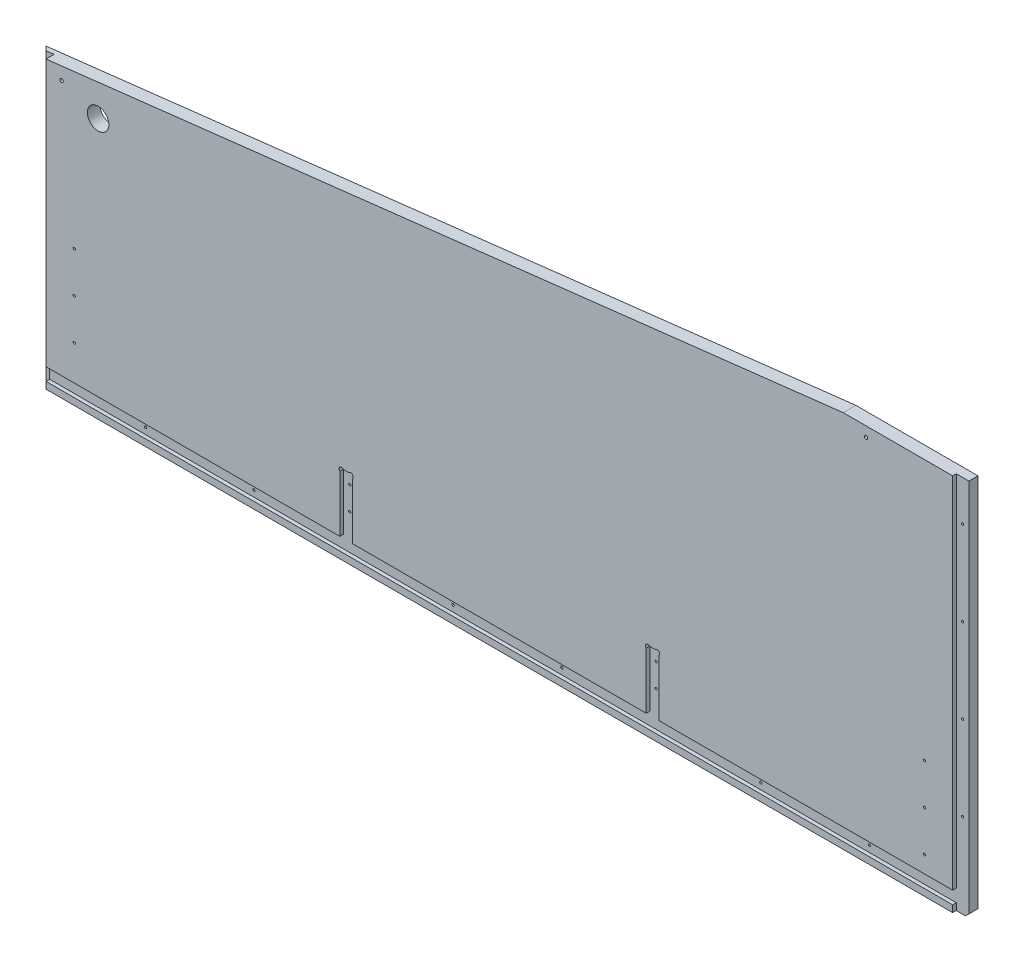
SolidWorks part; units mm, degrees
material "Pine"
ref_plane "Front Plane" through (0, 0, 0) normal (0, 0, 1) x (1, 0, 0)
ref_plane "Top Plane" through (0, 0, 0) normal (0, 1, 0) x (1, 0, 0)
ref_plane "Right Plane" through (0, 0, 0) normal (1, 0, 0) x (0, 0, -1)
sketch "Sketch1" plane through (0, 0, 0) normal (0, 0, 1) x (1, 0, 0)
  line L0 (8932.6508, -5243.5125) -> (10226.1458, -5243.5125)
  line L1 (9086.3208, -4722.0918) -> (10222.9708, -4853.7812)
  line L2 (8914.8708, -6342.0625) -> (10197.5708, -6342.0625)
  line L3 (8914.8708, -5808.6625) -> (10197.5708, -5808.6625)
  line L4 (8919.6333, -5253.0375) -> (10218.2083, -5253.0375)
  line L5 (9134.2633, -4656.1375) -> (9134.2633, -4638.3575)
  line L6 (9091.0833, -4638.3575) -> (9134.2633, -4638.3575)
  line L7 (9091.0833, -4567.2375) -> (9091.0833, -4638.3575)
  line L8 (9134.2633, -4656.1375) -> (9581.3033, -4656.1375)
  line L9 (9091.0833, -4567.2375) -> (9624.4833, -4567.2375)
  line L10 (9581.3033, -4656.1375) -> (9581.3033, -4638.3575)
  line L11 (9581.3033, -4638.3575) -> (9624.4833, -4638.3575)
  line L12 (9624.4833, -4567.2375) -> (9624.4833, -4638.3575)
  line L13 (8932.6508, -5225.7325) -> (9344.9775, -5225.7325)
  line L14 (8932.6508, -5256.2125) -> (8932.6508, -5243.5125)
  line L15 (8911.6958, -5256.2125) -> (8932.6508, -5256.2125)
  line L16 (8914.8708, -4722.0918) -> (9086.3208, -4722.0918)
  line L17 (8911.6958, -4715.5913) -> (8932.6508, -4715.5913)
  line L18 (8914.8708, -6342.0625) -> (8914.8708, -5808.6625)
  line L19 (12082.9917, -4722.0918) -> (10946.3417, -4853.7812)
  line L20 (12236.6617, -5243.5125) -> (10943.1667, -5243.5125)
  line L21 (10951.1042, -5253.0375) -> (12249.6792, -5253.0375)
  line L22 (10838.3917, -5656.2625) -> (11308.2917, -5656.2625)
  line L23 (10838.3917, -5719.7625) -> (11308.2917, -5719.7625)
  line L24 (10838.3917, -5742.5368) -> (11308.2917, -5742.5368)
  line L25 (10806.6417, -6342.0625) -> (11340.0417, -6342.0625)
  line L26 (10803.4667, -6335.7125) -> (11343.2167, -6335.7125)
  line L27 (10803.4667, -6317.9325) -> (11343.2167, -6317.9325)
  line L28 (10943.1667, -5225.7325) -> (11376.4483, -5225.7325)
  line L29 (11506.7292, -4754.5625) -> (10806.6417, -4827.5875)
  line L30 (11506.7292, -4567.2375) -> (11506.7292, -4754.5625)
  line L31 (10806.6417, -4567.2375) -> (10806.6417, -4827.5875)
  line L32 (10806.6417, -4567.2375) -> (11506.7292, -4567.2375)
  line L33 (10235.6708, -6329.3625) -> (10245.1958, -6329.3625)
  line L34 (10245.1958, -6329.3625) -> (10254.7208, -6278.5625)
  line L35 (10302.3458, -6329.3625) -> (10311.8708, -6278.5625)
  line L36 (10302.3458, -6329.3625) -> (10292.8208, -6329.3625)
  line L37 (10245.1958, -5821.3625) -> (10254.7208, -5872.1625)
  line L38 (10235.6708, -5821.3625) -> (10245.1958, -5821.3625)
  line L39 (10292.8208, -5821.3625) -> (10302.3458, -5821.3625)
  line L40 (10302.3458, -5821.3625) -> (10311.8708, -5872.1625)
  line L41 (10235.6708, -5821.3625) -> (10235.6708, -6329.3625)
  line L42 (10254.7208, -5872.1625) -> (10254.7208, -6278.5625)
  line L43 (10311.8708, -5872.1625) -> (10311.8708, -6278.5625)
  line L44 (10292.8208, -5821.3625) -> (10292.8208, -6329.3625)
  line L45 (8932.6508, -5225.7325) -> (8932.6508, -4715.5913)
  line L46 (8911.6958, -4715.5913) -> (8911.6958, -5256.2125)
  line L47 (8914.8708, -5248.275) -> (8914.8708, -4722.0918)
  line L48 (8919.6333, -5253.0375) -> (8914.8708, -5248.275)
  line L49 (8914.8708, -5145.0875) -> (8937.426, -5145.0875)
  line L50 (8914.8708, -5202.2375) -> (8937.426, -5202.2375)
  line L51 (10838.3917, -5656.2625) -> (10838.3917, -5719.7625)
  line L52 (10832.0417, -5736.1868) -> (10856.1717, -5736.1868)
  line L53 (10806.6417, -6342.0625) -> (10806.6417, -5818.7368)
  line L54 (10832.0417, -5649.9125) -> (10856.1717, -5649.9125)
  line L55 (10832.0417, -5726.1125) -> (10856.1717, -5726.1125)
  line L56 (10806.6417, -5818.7368) -> (10833.9015, -5818.7368)
  line L57 (10832.0417, -5806.0442) -> (10851.6815, -5806.0442)
  line L58 (10856.1717, -5801.5541) -> (10856.1717, -5736.1868)
  line L59 (10838.3917, -5814.2467) -> (10838.3917, -5742.5368)
  line L60 (10832.0417, -5806.0442) -> (10832.0417, -5736.1868)
  line L61 (10803.4667, -6317.9325) -> (10803.4667, -6335.7125)
  line L62 (10197.5708, -5808.6625) -> (10197.5708, -6342.0625)
  line L63 (9762.3842, -6348.4125) -> (9762.3842, -5802.3125)
  line L64 (9780.1642, -6348.4125) -> (9762.3842, -6348.4125)
  line L65 (9780.1642, -5802.3125) -> (9780.1642, -6348.4125)
  line L66 (9762.3842, -5802.3125) -> (9780.1642, -5802.3125)
  line L67 (9332.2775, -6348.4125) -> (9332.2775, -5802.3125)
  line L68 (9332.2775, -6348.4125) -> (9350.0575, -6348.4125)
  line L69 (9350.0575, -5802.3125) -> (9350.0575, -6348.4125)
  line L70 (9332.2775, -5802.3125) -> (9350.0575, -5802.3125)
  line L71 (9993.8374, -6061.075) -> (9993.8374, -6045.2418)
  line L72 (9998.5999, -6065.8375) -> (10014.4331, -6065.8375)
  line L73 (9998.5999, -6084.8875) -> (10014.4331, -6084.8875)
  line L74 (9993.8374, -6105.4832) -> (9993.8374, -6089.65)
  line L75 (9974.7874, -6105.4832) -> (9974.7874, -6089.65)
  line L76 (9954.1917, -6084.8875) -> (9970.0249, -6084.8875)
  line L77 (9974.7874, -6061.075) -> (9974.7874, -6045.2418)
  line L78 (9954.1917, -6065.8375) -> (9970.0249, -6065.8375)
  line L79 (10793.9417, -6237.2875) -> (10816.4969, -6237.2875)
  line L80 (10793.9417, -6294.4375) -> (10816.4969, -6294.4375)
  line L81 (10856.1717, -5649.9125) -> (10856.1717, -5726.1125)
  line L82 (10832.0417, -5726.1125) -> (10832.0417, -5649.9125)
  line L83 (10226.1458, -5225.7325) -> (10226.1458, -5243.5125)
  line L84 (10205.1908, -5257.8) -> (10205.1908, -4844.2499)
  line L85 (10230.9083, -4844.2499) -> (10230.9083, -5257.8)
  line L86 (10205.1908, -5257.8) -> (10230.9083, -5257.8)
  line L87 (10205.1908, -4844.2499) -> (10230.9083, -4844.2499)
  line L88 (10946.3417, -5176.8375) -> (10968.8969, -5176.8375)
  line L89 (9349.4676, -5141.9125) -> (9358.2674, -5141.9125)
  line L90 (10946.3417, -5119.6875) -> (10968.8969, -5119.6875)
  line L91 (9929.011, -4660.9635) -> (10066.0807, -4660.9635)
  line L92 (9929.011, -4678.7435) -> (10066.0807, -4678.7435)
  line L93 (10943.1667, -5225.7325) -> (10943.1667, -5243.5125)
  line L94 (10946.3417, -5248.275) -> (10951.1042, -5253.0375)
  line L95 (10946.3417, -5257.8063) -> (10946.3417, -4849.0188)
  line L96 (10964.1217, -5257.8) -> (10964.1217, -4844.2499)
  line L97 (10938.4042, -4844.2499) -> (10938.4042, -5257.8)
  line L98 (10938.4042, -5257.8) -> (10964.1217, -5257.8)
  line L99 (10964.1217, -4844.2499) -> (10938.4042, -4844.2499)
  line L100 (10344.8908, -4560.8875) -> (10369.0208, -4560.8875)
  line L101 (10344.8908, -4560.8875) -> (10369.0208, -4560.8875)
  line L102 (10800.2917, -4560.8875) -> (10824.4217, -4560.8875)
  line L103 (10200.4156, -5119.6875) -> (10222.9708, -5119.6875)
  line L104 (10200.4156, -5176.8375) -> (10222.9708, -5176.8375)
  line L105 (9344.9775, -5146.4026) -> (9344.9775, -5225.7325)
  line L106 (10344.8908, -4560.8875) -> (10344.8908, -4833.9375)
  line L107 (9792.8642, -5225.7325) -> (9792.8642, -5146.4026)
  line L108 (9362.7575, -5225.7325) -> (9775.0842, -5225.7325)
  line L109 (9680.3633, -4761.8396) -> (9680.3633, -4559.9604)
  line L110 (9656.2333, -4559.9604) -> (9680.3633, -4559.9604)
  line L111 (9656.2333, -4761.8396) -> (9680.3633, -4761.8396)
  line L112 (9656.2333, -4761.8396) -> (9656.2333, -4559.9604)
  line L113 (9779.5743, -5141.9125) -> (9788.374, -5141.9125)
  line L114 (10070.5708, -4665.4536) -> (10070.5708, -4674.2534)
  line L115 (9924.5208, -4674.2534) -> (9924.5208, -4665.4536)
  line L116 (12127.4417, -6188.3925) -> (12205.5015, -6188.3925)
  line L117 (12209.9917, -6170.6125) -> (12209.9917, -6183.9024)
  line L118 (9792.8642, -5225.7325) -> (10226.1458, -5225.7325)
  line L119 (9662.5833, -4754.5625) -> (10362.6708, -4827.5875)
  line L120 (9662.5833, -4567.2375) -> (9662.5833, -4754.5625)
  line L121 (10362.6708, -4567.2375) -> (10362.6708, -4827.5875)
  line L122 (9662.5833, -4567.2375) -> (10362.6708, -4567.2375)
  line L123 (10824.4217, -4833.9375) -> (10800.2917, -4833.9375)
  line L124 (10800.2917, -4833.9375) -> (10800.2917, -4560.8875)
  line L125 (10824.4217, -4560.8875) -> (10824.4217, -4833.9375)
  line L126 (10344.8908, -4833.9375) -> (10369.0208, -4833.9375)
  line L127 (10369.0208, -4833.9375) -> (10369.0208, -4560.8875)
  line L128 (10222.9708, -5248.275) -> (10218.2083, -5253.0375)
  line L129 (10222.9708, -5257.8063) -> (10222.9708, -4849.0188)
  line L130 (11734.6544, -5701.375) -> (11739.2301, -5701.375)
  line L131 (9362.7575, -5225.7325) -> (9362.7575, -5146.4026)
  line L132 (9775.0842, -5146.4026) -> (9775.0842, -5225.7325)
  line L133 (11761.3864, -5701.375) -> (11756.8282, -5701.375)
  line L134 (11734.6544, -5693.755) -> (11739.2301, -5693.755)
  line L135 (11761.4039, -5693.755) -> (11756.8282, -5693.755)
  line L136 (11734.6544, -5701.375) -> (11739.2301, -5701.375)
  line L137 (11744.3462, -5721.3024) -> (11744.3462, -5706.4179)
  line L138 (11751.7122, -5721.3024) -> (11751.7122, -5706.4179)
  line L139 (11740.0917, -6170.6125) -> (11740.0917, -6183.9024)
  line L140 (11689.2917, -6188.3925) -> (11822.6417, -6188.3925)
  line L141 (11689.2917, -6348.4093) -> (11689.2917, -6164.2657)
  line L142 (11689.2917, -6164.2657) -> (11746.4417, -6164.2657)
  line L143 (11746.4417, -6164.2657) -> (11746.4417, -6188.3925)
  line L144 (11689.2917, -6164.2657) -> (11746.4417, -6164.2657)
  line L145 (11340.0417, -5818.7368) -> (11340.0417, -6342.0625)
  line L146 (11290.5117, -5726.1125) -> (11314.6417, -5726.1125)
  line L147 (11290.5117, -5649.9125) -> (11290.5117, -5726.1125)
  line L148 (11340.0417, -5818.7368) -> (11312.7818, -5818.7368)
  line L149 (11314.6417, -5806.0442) -> (11295.0018, -5806.0442)
  line L150 (11290.5117, -5801.5541) -> (11290.5117, -5736.1868)
  line L151 (11308.2917, -5814.2467) -> (11308.2917, -5742.5368)
  line L152 (11314.6417, -5806.0442) -> (11314.6417, -5736.1868)
  line L153 (11290.5117, -5736.1868) -> (11314.6417, -5736.1868)
  line L154 (11848.0417, -6267.1325) -> (11962.3417, -6267.1325)
  line L155 (11962.3417, -6267.1325) -> (11962.3417, -6203.6325)
  line L156 (11343.2167, -6317.9325) -> (11343.2167, -6335.7125)
  line L157 (11365.4417, -5656.2625) -> (11365.4417, -5719.7625)
  line L158 (11365.4417, -5656.2625) -> (11479.7417, -5656.2625)
  line L159 (11778.1917, -6071.3937) -> (11802.3217, -6071.3937)
  line L160 (11314.6417, -5726.1125) -> (11314.6417, -5649.9125)
  line L161 (11314.6417, -5649.9125) -> (11290.5117, -5649.9125)
  line L162 (11308.2917, -5719.7625) -> (11308.2917, -5656.2625)
  line L163 (11689.2917, -6348.4093) -> (11713.4217, -6348.4093)
  line L164 (12203.6417, -6164.2657) -> (12260.7917, -6164.2657)
  line L165 (11713.4217, -6348.4093) -> (11713.4217, -6164.2657)
  line L166 (11695.6417, -6342.0625) -> (11695.6417, -6170.6125)
  line L167 (11695.6417, -6048.5337) -> (11699.4517, -6052.3437)
  line L168 (11822.6417, -6292.5325) -> (11822.6417, -6188.3925)
  line L169 (11695.6417, -6342.0625) -> (11695.6417, -6170.6125)
  line L170 (11848.0417, -6203.6325) -> (11962.3417, -6203.6325)
  line L171 (11848.0417, -6203.6325) -> (11848.0417, -6267.1325)
  line L172 (11987.7417, -6267.1325) -> (11987.7417, -6203.6325)
  line L173 (11784.5417, -6077.7437) -> (11784.5417, -6141.2438)
  line L174 (11517.8417, -5656.2625) -> (11632.1417, -5656.2625)
  line L175 (11632.1417, -5656.2625) -> (11632.1417, -5719.7625)
  line L176 (11632.1417, -5719.7625) -> (11517.8417, -5719.7625)
  line L177 (11517.8417, -5719.7625) -> (11517.8417, -5656.2625)
  line L178 (11692.4667, -6028.2137) -> (11692.4667, -6045.9937)
  line L179 (11695.6417, -5979.3188) -> (11718.1969, -5979.3188)
  line L180 (11695.6417, -5922.1687) -> (11718.1969, -5922.1687)
  line L181 (11821.0415, -5722.9375) -> (11821.0415, -5943.6)
  line L182 (11687.7042, -5651.5) -> (11701.9917, -5651.5)
  line L183 (11687.7042, -5651.5) -> (11687.7042, -6055.5251)
  line L184 (11687.7042, -6055.5251) -> (11701.9917, -6055.5251)
  line L185 (11701.9917, -6055.5251) -> (11701.9917, -5651.5)
  line L186 (11695.6417, -6055.2013) -> (11695.6417, -5649.595)
  line L187 (11695.6417, -5656.2625) -> (11695.6417, -6048.5337)
  line L188 (11695.6417, -6170.6125) -> (11740.0917, -6170.6125)
  line L189 (12203.6417, -6164.2657) -> (12203.6417, -6188.3925)
  line L190 (12254.4417, -6342.0625) -> (12254.4417, -6170.6125)
  line L191 (12129.0419, -5943.6) -> (12129.0419, -5722.9375)
  line L192 (12254.4417, -6048.5337) -> (12250.6317, -6052.3437)
  line L193 (12257.6167, -6045.9937) -> (12257.6167, -6028.2137)
  line L194 (12248.0917, -5651.5) -> (12262.3792, -5651.5)
  line L195 (12262.3792, -5651.5) -> (12262.3792, -6055.5251)
  line L196 (12262.3792, -6055.5251) -> (12248.0917, -6055.5251)
  line L197 (12248.0917, -6055.5251) -> (12248.0917, -5651.5)
  line L198 (12254.4417, -6141.2438) -> (12254.4417, -6077.7437)
  line L199 (12236.6617, -6164.2657) -> (12260.7917, -6164.2657)
  line L200 (12102.0417, -6267.1325) -> (11987.7417, -6267.1325)
  line L201 (11330.1865, -6237.2875) -> (11352.7417, -6237.2875)
  line L202 (11330.1865, -6294.4375) -> (11352.7417, -6294.4375)
  line L203 (11474.6617, -5851.8425) -> (11492.4417, -5851.8425)
  line L204 (11474.6617, -5808.6625) -> (11474.6617, -5851.8425)
  line L205 (11403.5417, -5808.6625) -> (11474.6617, -5808.6625)
  line L206 (11492.4417, -5851.8425) -> (11492.4417, -6298.8825)
  line L207 (11403.5417, -6342.0625) -> (11403.5417, -5808.6625)
  line L208 (11474.6617, -6298.8825) -> (11492.4417, -6298.8825)
  line L209 (11474.6617, -6342.0625) -> (11474.6617, -6298.8825)
  line L210 (11403.5417, -6342.0625) -> (11474.6617, -6342.0625)
  line L211 (11619.4417, -5851.8425) -> (11601.6617, -5851.8425)
  line L212 (11601.6617, -5808.6625) -> (11601.6617, -5851.8425)
  line L213 (11530.5417, -5808.6625) -> (11601.6617, -5808.6625)
  line L214 (11619.4417, -5851.8425) -> (11619.4417, -6298.8825)
  line L215 (11530.5417, -6342.0625) -> (11530.5417, -5808.6625)
  line L216 (11619.4417, -6298.8825) -> (11601.6617, -6298.8825)
  line L217 (11601.6617, -6342.0625) -> (11601.6617, -6298.8825)
  line L218 (11530.5417, -6342.0625) -> (11601.6617, -6342.0625)
  line L219 (11479.7417, -5719.7625) -> (11479.7417, -5656.2625)
  line L220 (11365.4417, -5719.7625) -> (11479.7417, -5719.7625)
  line L221 (11778.1917, -6147.5937) -> (11802.3217, -6147.5937)
  line L222 (11802.3217, -6071.3937) -> (11802.3217, -6147.5937)
  line L223 (11778.1917, -6147.5937) -> (11778.1917, -6071.3937)
  line L224 (12254.4417, -5922.1687) -> (12231.8865, -5922.1687)
  line L225 (12254.4417, -5979.3188) -> (12231.8865, -5979.3188)
  line L226 (12254.4417, -6055.2013) -> (12254.4417, -5649.595)
  line L227 (12254.4417, -6048.5337) -> (12254.4417, -5656.2625)
  line L228 (11841.6917, -5702.2873) -> (12108.3917, -5702.2873)
  line L229 (11822.6417, -6292.5325) -> (12127.4417, -6292.5325)
  line L230 (12127.4417, -6292.5325) -> (12127.4417, -6188.3925)
  line L231 (12254.4417, -6170.6125) -> (12209.9917, -6170.6125)
  line L232 (11695.6417, -6342.0625) -> (12254.4417, -6342.0625)
  line L233 (12236.6617, -6348.4093) -> (12260.7917, -6348.4093)
  line L234 (12260.7917, -6348.4093) -> (12260.7917, -6164.2657)
  line L235 (12236.6617, -6348.4093) -> (12236.6617, -6164.2657)
  line L236 (12102.0417, -6203.6325) -> (12102.0417, -6267.1325)
  line L237 (11987.7417, -6203.6325) -> (12102.0417, -6203.6325)
  line L238 (12236.6617, -6147.5937) -> (12236.6617, -6071.3937)
  line L239 (12203.6417, -6188.3925) -> (12260.7917, -6188.3925)
  line L240 (11098.7417, -4665.4536) -> (11098.7417, -4674.2534)
  line L241 (11394.2283, -5146.4026) -> (11394.2283, -5225.7325)
  line L242 (11376.4483, -5225.7325) -> (11376.4483, -5146.4026)
  line L243 (11394.2283, -5225.7325) -> (11806.555, -5225.7325)
  line L244 (11841.6917, -5964.2502) -> (12108.3917, -5964.2502)
  line L245 (12236.6617, -6147.5937) -> (12260.7917, -6147.5937)
  line L246 (12236.6617, -5256.2125) -> (12236.6617, -5243.5125)
  line L247 (12260.7917, -6147.5937) -> (12260.7917, -6071.3937)
  line L248 (12260.7917, -6071.3937) -> (12236.6617, -6071.3937)
  line L249 (12254.4417, -6077.7437) -> (11784.5417, -6077.7437)
  line L250 (11784.5417, -6141.2438) -> (12254.4417, -6141.2438)
  line L252 (12254.4417, -5656.2625) -> (11695.6417, -5656.2625)
  line L253 (11699.4517, -6052.3437) -> (12250.6317, -6052.3437)
  line L254 (11692.4667, -6045.9937) -> (12257.6167, -6045.9937)
  line L255 (11692.4667, -6028.2137) -> (12257.6167, -6028.2137)
  line L256 (11824.335, -5146.4026) -> (11824.335, -5225.7325)
  line L257 (11811.0451, -5141.9125) -> (11819.8449, -5141.9125)
  line L258 (11244.7917, -4674.2534) -> (11244.7917, -4665.4536)
  line L259 (11806.555, -5225.7325) -> (11806.555, -5146.4026)
  line L260 (11488.9492, -4761.8396) -> (11488.9492, -4559.9604)
  line L261 (11488.9492, -4559.9604) -> (11513.0792, -4559.9604)
  line L262 (11488.9492, -4761.8396) -> (11513.0792, -4761.8396)
  line L263 (11513.0792, -4761.8396) -> (11513.0792, -4559.9604)
  line L264 (11240.3015, -4660.9635) -> (11103.2318, -4660.9635)
  line L265 (11103.2318, -4678.7435) -> (11240.3015, -4678.7435)
  line L266 (12236.6617, -5225.7325) -> (12236.6617, -4715.5913)
  line L267 (12257.6167, -4715.5913) -> (12257.6167, -5256.2125)
  line L268 (12254.4417, -5248.275) -> (12254.4417, -4722.0918)
  line L269 (12236.6617, -5225.7325) -> (11824.335, -5225.7325)
  line L270 (12035.0492, -4656.1375) -> (12035.0492, -4638.3575)
  line L271 (12078.2292, -4638.3575) -> (12035.0492, -4638.3575)
  line L272 (12078.2292, -4567.2375) -> (12078.2292, -4638.3575)
  line L273 (12035.0492, -4656.1375) -> (11588.0092, -4656.1375)
  line L274 (11544.8292, -4567.2375) -> (12078.2292, -4567.2375)
  line L275 (11588.0092, -4656.1375) -> (11588.0092, -4638.3575)
  line L276 (11544.8292, -4638.3575) -> (11588.0092, -4638.3575)
  line L277 (11544.8292, -4567.2375) -> (11544.8292, -4638.3575)
  line L278 (12249.6792, -5253.0375) -> (12254.4417, -5248.275)
  line L280 (12257.6167, -5256.2125) -> (12236.6617, -5256.2125)
  line L281 (12231.8865, -5145.0875) -> (12254.4417, -5145.0875)
  line L282 (12231.8865, -5202.2375) -> (12254.4417, -5202.2375)
  line L283 (12236.6617, -4715.5913) -> (12257.6167, -4715.5913)
  line L284 (12082.9917, -4722.0918) -> (12254.4417, -4722.0918)
  line L285 (11380.9385, -5141.9125) -> (11389.7382, -5141.9125)
  circle A0 centre (8923.7608, -4778.9042) radius 1.5875
  circle A1 centre (9062.6598, -4736.3765) radius 2.3685
  circle A2 centre (9051.3958, -6281.7375) radius 22.225
  circle A3 centre (9083.1458, -6249.9875) radius 1.5875
  circle A4 centre (9083.1458, -6313.4875) radius 1.5875
  circle A5 centre (9019.6458, -6249.9875) radius 1.5875
  circle A6 centre (9019.6458, -6313.4875) radius 1.5875
  circle A7 centre (8972.3383, -5202.2375) radius 1.5875
  circle A8 centre (8923.7608, -5015.9708) radius 1.5875
  circle A9 centre (8923.7608, -5134.5042) radius 1.5875
  circle A10 centre (9054.5708, -5234.6225) radius 1.5875
  circle A11 centre (8923.7608, -4897.4375) radius 1.5875
  circle A12 centre (8972.3383, -5087.9375) radius 1.5875
  circle A13 centre (8972.3383, -5145.0875) radius 1.5875
  circle A14 centre (10847.2817, -5668.9625) radius 1.5875
  circle A15 centre (10847.2817, -5707.0625) radius 1.5875
  circle A16 centre (10847.2817, -5755.2368) radius 1.5875
  circle A17 centre (10851.4092, -6237.2875) radius 1.5875
  circle A18 centre (10851.4092, -6294.4375) radius 1.5875
  circle A19 centre (10847.2817, -5793.3442) radius 1.5875
  arc A20 (10833.9015, -5818.7368) -> (10838.3917, -5814.2467) centre (10836.1466, -5816.4918) ccw
  arc A21 (10851.6815, -5806.0442) -> (10856.1717, -5801.5541) centre (10853.9266, -5803.7992) ccw
  circle A22 centre (10882.8417, -6040.4375) radius 1.5875
  circle A23 centre (10882.8417, -6218.2375) radius 1.5875
  circle A24 centre (10882.8417, -5862.6375) radius 1.5875
  circle A25 centre (10908.2417, -6326.8225) radius 1.5875
  circle A26 centre (10908.2417, -6326.8225) radius 1.5875
  circle A27 centre (10851.4092, -6180.1375) radius 1.5875
  circle A28 centre (10815.5317, -4783.4231) radius 1.5875
  circle A29 centre (10815.5317, -4696.9488) radius 1.5875
  circle A30 centre (10815.5317, -4610.4746) radius 1.5875
  circle A31 centre (10979.1323, -4867.0082) radius 2.3685
  circle A32 centre (10190.1802, -4867.0082) radius 2.3685
  circle A33 centre (10955.2317, -4929.9812) radius 1.5875
  circle A34 centre (10955.2317, -5031.5812) radius 1.5875
  circle A35 centre (10214.0808, -4929.9812) radius 1.5875
  circle A36 centre (10214.0808, -5031.5812) radius 1.5875
  circle A37 centre (9341.1675, -6265.8625) radius 1.5875
  circle A38 centre (9771.2742, -5884.8625) radius 1.5875
  circle A39 centre (9771.2742, -6138.8625) radius 1.5875
  circle A40 centre (9771.2742, -6011.8625) radius 1.5875
  arc A41 (10036.2287, -6113.8083) -> (10051.3426, -6111.6033) centre (10042.9639, -6107.0732) ccw
  arc A42 (10051.3426, -6111.6033) -> (10051.3426, -6039.1217) centre (9984.3124, -6075.3625) ccw
  arc A43 (10051.3426, -6039.1217) -> (10036.2287, -6036.9167) centre (10042.9639, -6043.6518) ccw
  arc A44 (10034.5851, -6102.5431) -> (10034.5851, -6048.1819) centre (9984.3124, -6075.3625) ccw
  arc A45 (10034.5851, -6102.5431) -> (10036.2287, -6113.8083) centre (10042.9639, -6107.0732) ccw
  arc A46 (10036.2287, -6036.9167) -> (10034.5851, -6048.1819) centre (10042.9639, -6043.6518) ccw
  arc A47 (9945.8666, -6127.2787) -> (9948.0717, -6142.3927) centre (9952.6018, -6134.0139) ccw
  arc A48 (9948.0717, -6142.3927) -> (10020.5532, -6142.3927) centre (9984.3124, -6075.3625) ccw
  arc A49 (10020.5532, -6142.3927) -> (10022.7583, -6127.2787) centre (10016.0231, -6134.0139) ccw
  arc A50 (9957.1319, -6125.6352) -> (10011.493, -6125.6352) centre (9984.3124, -6075.3625) ccw
  arc A51 (9957.1319, -6125.6352) -> (9945.8666, -6127.2787) centre (9952.6018, -6134.0139) ccw
  arc A52 (10022.7583, -6127.2787) -> (10011.493, -6125.6352) centre (10016.0231, -6134.0139) ccw
  arc A53 (9932.3962, -6036.9167) -> (9917.2822, -6039.1217) centre (9925.661, -6043.6518) ccw
  arc A54 (9917.2822, -6039.1217) -> (9917.2822, -6111.6033) centre (9984.3124, -6075.3625) ccw
  arc A55 (9917.2822, -6111.6033) -> (9932.3962, -6113.8083) centre (9925.661, -6107.0732) ccw
  arc A56 (9934.0398, -6048.1819) -> (9934.0398, -6102.5431) centre (9984.3124, -6075.3625) ccw
  arc A57 (9934.0398, -6048.1819) -> (9932.3962, -6036.9167) centre (9925.661, -6043.6518) ccw
  arc A58 (9932.3962, -6113.8083) -> (9934.0398, -6102.5431) centre (9925.661, -6107.0732) ccw
  arc A59 (9945.8666, -6023.4463) -> (9957.1319, -6025.0898) centre (9952.6018, -6016.7111) ccw
  arc A60 (10011.493, -6025.0898) -> (10022.7583, -6023.4463) centre (10016.0231, -6016.7111) ccw
  arc A61 (10011.493, -6025.0898) -> (9957.1319, -6025.0898) centre (9984.3124, -6075.3625) ccw
  arc A62 (9948.0717, -6008.3323) -> (9945.8666, -6023.4463) centre (9952.6018, -6016.7111) ccw
  arc A63 (10020.5532, -6008.3323) -> (9948.0717, -6008.3323) centre (9984.3124, -6075.3625) ccw
  arc A64 (10022.7583, -6023.4463) -> (10020.5532, -6008.3323) centre (10016.0231, -6016.7111) ccw
  arc A65 (10005.0943, -6187.7574) -> (10096.7073, -6096.1443) centre (9984.3124, -6075.3625) ccw
  arc A66 (9993.8374, -6178.3911) -> (10005.0943, -6187.7574) centre (10003.3624, -6178.3911) ccw
  arc A67 (10001.6306, -6169.0249) -> (10077.9748, -6092.6807) centre (9984.3124, -6075.3625) ccw
  arc A68 (10087.3411, -6084.8875) -> (10077.9748, -6092.6807) centre (10087.3411, -6094.4125) ccw
  arc A69 (10001.6306, -6169.0249) -> (9993.8374, -6178.3911) centre (10003.3624, -6178.3911) ccw
  arc A70 (9963.5306, -6187.7574) -> (9974.7874, -6178.3911) centre (9965.2624, -6178.3911) ccw
  arc A71 (9871.9176, -6096.1443) -> (9963.5306, -6187.7574) centre (9984.3124, -6075.3625) ccw
  arc A72 (9881.2838, -6084.8875) -> (9871.9176, -6096.1443) centre (9881.2838, -6094.4125) ccw
  arc A73 (9890.65, -6092.6807) -> (9966.9943, -6169.0249) centre (9984.3124, -6075.3625) ccw
  arc A74 (9974.7874, -6178.3911) -> (9966.9943, -6169.0249) centre (9965.2624, -6178.3911) ccw
  arc A75 (9890.65, -6092.6807) -> (9881.2838, -6084.8875) centre (9881.2838, -6094.4125) ccw
  arc A76 (9871.9176, -6054.5807) -> (9881.2838, -6065.8375) centre (9881.2838, -6056.3125) ccw
  arc A77 (9963.5306, -5962.9676) -> (9871.9176, -6054.5807) centre (9984.3124, -6075.3625) ccw
  arc A78 (9974.7874, -5972.3339) -> (9963.5306, -5962.9676) centre (9965.2624, -5972.3339) ccw
  arc A79 (9966.9943, -5981.7001) -> (9890.65, -6058.0443) centre (9984.3124, -6075.3625) ccw
  arc A80 (9881.2838, -6065.8375) -> (9890.65, -6058.0443) centre (9881.2838, -6056.3125) ccw
  arc A81 (9966.9943, -5981.7001) -> (9974.7874, -5972.3339) centre (9965.2624, -5972.3339) ccw
  arc A82 (10077.9748, -6058.0443) -> (10087.3411, -6065.8375) centre (10087.3411, -6056.3125) ccw
  arc A83 (9993.8374, -5972.3339) -> (10001.6306, -5981.7001) centre (10003.3624, -5972.3339) ccw
  arc A84 (10077.9748, -6058.0443) -> (10001.6306, -5981.7001) centre (9984.3124, -6075.3625) ccw
  arc A85 (10087.3411, -6065.8375) -> (10096.7073, -6054.5807) centre (10087.3411, -6056.3125) ccw
  arc A86 (10096.7073, -6054.5807) -> (10005.0943, -5962.9676) centre (9984.3124, -6075.3625) ccw
  arc A87 (10005.0943, -5962.9676) -> (9993.8374, -5972.3339) centre (10003.3624, -5972.3339) ccw
  arc A88 (10014.4331, -6065.8375) -> (10018.7361, -6059.0339) centre (10014.4331, -6061.075) ccw
  arc A89 (10018.7361, -6059.0339) -> (10000.641, -6040.9388) centre (9984.3124, -6075.3625) ccw
  arc A90 (10000.641, -6040.9388) -> (9993.8374, -6045.2418) centre (9998.5999, -6045.2418) ccw
  arc A91 (9993.8374, -6061.075) -> (9998.5999, -6065.8375) centre (9998.5999, -6061.075) ccw
  arc A92 (9993.8374, -6105.4832) -> (10000.641, -6109.7862) centre (9998.5999, -6105.4832) ccw
  arc A93 (10000.641, -6109.7862) -> (10018.7361, -6091.6911) centre (9984.3124, -6075.3625) ccw
  arc A94 (10018.7361, -6091.6911) -> (10014.4331, -6084.8875) centre (10014.4331, -6089.65) ccw
  arc A95 (9998.5999, -6084.8875) -> (9993.8374, -6089.65) centre (9998.5999, -6089.65) ccw
  arc A96 (9954.1917, -6084.8875) -> (9949.8888, -6091.6911) centre (9954.1917, -6089.65) ccw
  arc A97 (9949.8888, -6091.6911) -> (9967.9839, -6109.7862) centre (9984.3124, -6075.3625) ccw
  arc A98 (9967.9839, -6109.7862) -> (9974.7874, -6105.4832) centre (9970.0249, -6105.4832) ccw
  arc A99 (9974.7874, -6089.65) -> (9970.0249, -6084.8875) centre (9970.0249, -6089.65) ccw
  arc A100 (9970.0249, -6065.8375) -> (9974.7874, -6061.075) centre (9970.0249, -6061.075) ccw
  arc A101 (9949.8888, -6059.0339) -> (9954.1917, -6065.8375) centre (9954.1917, -6061.075) ccw
  arc A102 (9967.9839, -6040.9388) -> (9949.8888, -6059.0339) centre (9984.3124, -6075.3625) ccw
  arc A103 (9974.7874, -6045.2418) -> (9967.9839, -6040.9388) centre (9970.0249, -6045.2418) ccw
  arc A104 (10096.7073, -6096.1443) -> (10087.3411, -6084.8875) centre (10087.3411, -6094.4125) ccw
  circle A105 centre (9771.2742, -6265.8625) radius 1.5875
  circle A106 centre (9341.1675, -5884.8625) radius 1.5875
  circle A107 centre (9341.1675, -6138.8625) radius 1.5875
  circle A108 centre (9341.1675, -6011.8625) radius 1.5875
  circle A109 centre (11037.2315, -4887.5494) radius 15.0812
  arc A110 (9349.4676, -5141.9125) -> (9344.9775, -5146.4026) centre (9347.2226, -5144.1576) ccw
  arc A111 (9362.7575, -5146.4026) -> (9358.2674, -5141.9125) centre (9360.5124, -5144.1576) ccw
  circle A112 centre (9946.7458, -4669.8535) radius 1.5875
  arc A113 (9924.5208, -4674.2534) -> (9929.011, -4678.7435) centre (9926.7659, -4676.4984) ccw
  circle A114 centre (11003.8092, -5176.8375) radius 1.5875
  circle A115 centre (11003.8092, -5119.6875) radius 1.5875
  circle A116 centre (10353.7808, -4696.9488) radius 1.5875
  circle A117 centre (10353.7808, -4610.4746) radius 1.5875
  circle A118 centre (10353.7808, -4783.4231) radius 1.5875
  circle A119 centre (11003.8092, -5062.5375) radius 1.5875
  circle A120 centre (9353.8675, -5160.9625) radius 1.5875
  circle A121 centre (9638.7708, -5234.6225) radius 1.5875
  circle A122 centre (9671.4733, -4724.1144) radius 1.5875
  circle A123 centre (9671.4733, -4661.3637) radius 1.5875
  circle A124 centre (9671.4733, -4598.6129) radius 1.5875
  arc A125 (9792.8642, -5146.4026) -> (9788.374, -5141.9125) centre (9790.6191, -5144.1576) ccw
  arc A126 (9779.5743, -5141.9125) -> (9775.0842, -5146.4026) centre (9777.3292, -5144.1576) ccw
  circle A127 centre (10048.3458, -4669.8535) radius 1.5875
  arc A128 (10070.5708, -4665.4536) -> (10066.0807, -4660.9635) centre (10068.3258, -4663.2086) ccw
  arc A129 (10066.0807, -4678.7435) -> (10070.5708, -4674.2534) centre (10068.3258, -4676.4984) ccw
  circle A130 centre (9997.5458, -4669.8535) radius 1.5875
  arc A131 (9929.011, -4660.9635) -> (9924.5208, -4665.4536) centre (9926.7659, -4663.2086) ccw
  circle A132 centre (10132.081, -4887.5494) radius 15.0812
  circle A133 centre (10165.5033, -5176.8375) radius 1.5875
  circle A134 centre (10165.5033, -5119.6875) radius 1.5875
  circle A135 centre (9486.3708, -5234.6225) radius 1.5875
  circle A136 centre (10165.5033, -5062.5375) radius 1.5875
  circle A137 centre (9206.9708, -5234.6225) radius 1.5875
  circle A138 centre (10070.5708, -5234.6225) radius 1.5875
  circle A139 centre (9918.1708, -5234.6225) radius 1.5875
  circle A140 centre (9783.9742, -5160.9625) radius 1.5875
  circle A141 centre (9783.9742, -5193.9825) radius 1.5875
  circle A142 centre (9353.8675, -5193.9825) radius 1.5875
  circle A143 centre (11073.3417, -6326.8225) radius 1.5875
  circle A144 centre (11073.3417, -6326.8225) radius 1.5875
  circle A145 centre (11295.2742, -6180.1375) radius 1.5875
  circle A146 centre (11295.2742, -6294.4375) radius 1.5875
  circle A147 centre (11295.2742, -6237.2875) radius 1.5875
  circle A148 centre (11975.0417, -5692.775) radius 3.4925
  circle A149 centre (11263.8417, -5862.6375) radius 1.5875
  arc A150 (11739.2301, -5701.375) -> (11744.3462, -5706.4179) centre (11748.0292, -5697.565) ccw
  arc A151 (11751.7122, -5706.4179) -> (11756.8282, -5701.375) centre (11748.0292, -5697.565) ccw
  arc A152 (11744.3462, -5721.3024) -> (11751.7122, -5721.3024) centre (11748.0292, -5725.505) ccw
  arc A153 (11734.6544, -5693.755) -> (11724.9787, -5697.565) centre (11730.5667, -5697.565) ccw
  arc A154 (11756.8282, -5693.755) -> (11739.2301, -5693.755) centre (11748.0292, -5697.565) ccw
  arc A155 (11724.9787, -5697.565) -> (11734.6544, -5701.375) centre (11730.5667, -5697.565) ccw
  arc A156 (11761.3864, -5701.375) -> (11771.0797, -5697.565) centre (11765.4842, -5697.565) ccw
  arc A157 (11771.0797, -5697.565) -> (11761.4039, -5693.755) centre (11765.4917, -5697.565) ccw
  arc A158 (11740.0917, -6183.9024) -> (11744.5818, -6188.3925) centre (11742.3367, -6186.1474) ccw
  arc A159 (12205.5015, -6188.3925) -> (12209.9917, -6183.9024) centre (12207.7466, -6186.1474) ccw
  circle A160 centre (11299.4017, -5793.3442) radius 1.5875
  arc A161 (11308.2917, -5814.2467) -> (11312.7818, -5818.7368) centre (11310.5367, -5816.4918) ccw
  arc A162 (11290.5117, -5801.5541) -> (11295.0018, -5806.0442) centre (11292.7567, -5803.7992) ccw
  circle A163 centre (11704.5317, -6314.149) radius 1.5875
  circle A164 centre (11748.9817, -6208.7125) radius 1.5875
  circle A165 centre (11263.8417, -6218.2375) radius 1.5875
  circle A166 centre (11263.8417, -6040.4375) radius 1.5875
  circle A167 centre (11238.4417, -6326.8225) radius 1.5875
  circle A168 centre (11238.4417, -6326.8225) radius 1.5875
  circle A169 centre (11299.4017, -5668.9625) radius 1.5875
  circle A170 centre (11299.4017, -5707.0625) radius 1.5875
  circle A171 centre (11726.7567, -6179.5025) radius 1.5875
  circle A172 centre (11704.5317, -6199.3198) radius 1.5875
  circle A173 centre (11748.9817, -6272.2125) radius 1.5875
  circle A174 centre (11704.5317, -6256.7344) radius 1.5875
  circle A175 centre (11299.4017, -5755.2368) radius 1.5875
  circle A176 centre (11913.4467, -6301.4225) radius 1.5875
  circle A177 centre (11790.2567, -6301.4225) radius 1.5875
  circle A178 centre (11793.4317, -6128.5437) radius 1.5875
  circle A179 centre (11753.1092, -5865.0188) radius 1.5875
  circle A180 centre (11809.9417, -6037.1038) radius 1.5875
  circle A181 centre (11809.9417, -6037.1038) radius 1.5875
  circle A182 centre (11753.1092, -5922.1687) radius 1.5875
  circle A183 centre (11975.0417, -5973.7625) radius 3.4925
  circle A184 centre (11975.0417, -6037.1038) radius 1.5875
  circle A185 centre (11753.1092, -5979.3188) radius 1.5875
  circle A186 centre (11975.0417, -6037.1038) radius 1.5875
  arc A187 (11841.6917, -5702.2873) -> (11821.0415, -5722.9375) centre (11841.6917, -5722.9375) ccw
  circle A188 centre (11811.5292, -5833.2687) radius 3.4925
  arc A189 (11821.0415, -5943.6) -> (11841.6917, -5964.2502) centre (11841.6917, -5943.6) ccw
  circle A190 centre (12196.9742, -5865.0188) radius 1.5875
  arc A191 (12129.0419, -5722.9375) -> (12108.3917, -5702.2873) centre (12108.3917, -5722.9375) ccw
  circle A192 centre (12036.6367, -6301.4225) radius 1.5875
  circle A193 centre (12159.8267, -6301.4225) radius 1.5875
  circle A194 centre (12138.5542, -5833.2687) radius 3.4925
  circle A195 centre (12197.2917, -5761.0375) radius 15.0812
  circle A196 centre (11793.4317, -6090.4437) radius 1.5875
  circle A197 centre (12196.9742, -5922.1687) radius 1.5875
  arc A198 (12108.3917, -5964.2502) -> (12129.0419, -5943.6) centre (12108.3917, -5943.6) ccw
  circle A199 centre (12196.9742, -5979.3188) radius 1.5875
  circle A200 centre (12201.1017, -6272.2125) radius 1.5875
  circle A201 centre (12245.5517, -6314.149) radius 1.5875
  circle A202 centre (12245.5517, -6256.7344) radius 1.5875
  circle A203 centre (12201.1017, -6208.7125) radius 1.5875
  circle A204 centre (12223.3267, -6179.5025) radius 1.5875
  circle A205 centre (12245.5517, -6199.3198) radius 1.5875
  circle A206 centre (11171.7667, -4669.8535) radius 1.5875
  circle A207 centre (11222.5667, -4669.8535) radius 1.5875
  arc A208 (11240.3015, -4678.7435) -> (11244.7917, -4674.2534) centre (11242.5466, -4676.4984) ccw
  circle A209 centre (11385.3383, -5193.9825) radius 1.5875
  circle A210 centre (12106.6527, -4736.3765) radius 2.3685
  circle A211 centre (12140.1417, -6037.1038) radius 1.5875
  circle A212 centre (12140.1417, -6037.1038) radius 1.5875
  circle A213 centre (12245.5517, -6090.4437) radius 1.5875
  circle A214 centre (12245.5517, -6128.5437) radius 1.5875
  circle A215 centre (11385.3383, -5160.9625) radius 1.5875
  arc A216 (11824.335, -5146.4026) -> (11819.8449, -5141.9125) centre (11822.0899, -5144.1576) ccw
  arc A217 (11811.0451, -5141.9125) -> (11806.555, -5146.4026) centre (11808.8001, -5144.1576) ccw
  circle A218 centre (11815.445, -5193.9825) radius 1.5875
  circle A219 centre (11815.445, -5160.9625) radius 1.5875
  circle A220 centre (11530.5417, -5234.6225) radius 1.5875
  circle A221 centre (11962.3417, -5234.6225) radius 1.5875
  arc A222 (11244.7917, -4665.4536) -> (11240.3015, -4660.9635) centre (11242.5466, -4663.2086) ccw
  circle A223 centre (11682.9417, -5234.6225) radius 1.5875
  circle A224 centre (11497.8392, -4724.1144) radius 1.5875
  circle A225 centre (11497.8392, -4661.3637) radius 1.5875
  circle A226 centre (11497.8392, -4598.6129) radius 1.5875
  circle A227 centre (11120.9667, -4669.8535) radius 1.5875
  arc A228 (11103.2318, -4660.9635) -> (11098.7417, -4665.4536) centre (11100.9867, -4663.2086) ccw
  arc A229 (11098.7417, -4674.2534) -> (11103.2318, -4678.7435) centre (11100.9867, -4676.4984) ccw
  circle A230 centre (12196.9742, -5202.2375) radius 1.5875
  circle A231 centre (12245.5517, -5015.9708) radius 1.5875
  circle A232 centre (12245.5517, -5134.5042) radius 1.5875
  circle A233 centre (12114.7417, -5234.6225) radius 1.5875
  circle A234 centre (12245.5517, -4897.4375) radius 1.5875
  circle A235 centre (12245.5517, -4778.9042) radius 1.5875
  circle A236 centre (12196.9742, -5087.9375) radius 1.5875
  circle A237 centre (12196.9742, -5145.0875) radius 1.5875
  circle A238 centre (11098.7417, -5234.6225) radius 1.5875
  circle A239 centre (11251.1417, -5234.6225) radius 1.5875
  arc A240 (11380.9385, -5141.9125) -> (11376.4483, -5146.4026) centre (11378.6934, -5144.1576) ccw
  arc A241 (11394.2283, -5146.4026) -> (11389.7382, -5141.9125) centre (11391.9833, -5144.1576) ccw
sketch "Sketch2" plane through (0, 0, 0) normal (0, 0, 1) x (1, 0, 0)
  line L0 (10946.3417, -4853.7812) -> (10946.3417, -5248.275)
  line L1 (10946.3417, -5248.275) -> (10951.1042, -5253.0375)
  line L2 (10951.1042, -5253.0375) -> (12249.6792, -5253.0375)
  line L3 (12249.6792, -5253.0375) -> (12254.4417, -5248.275)
  line L4 (12254.4417, -5248.275) -> (12254.4417, -4722.0918)
  line L5 (12254.4417, -4722.0918) -> (12082.9917, -4722.0918)
  line L6 (12082.9917, -4722.0918) -> (12254.4417, -4722.0918) construction
  line L7 (12082.9917, -4722.0918) -> (10946.3417, -4853.7812) construction
  line L8 (12082.9917, -4722.0918) -> (10946.3417, -4853.7812)
extrude "Extrude1" add sketch "Sketch2" against normal blind 17.78
sketch "Sketch3" plane through (0, 0, 0) normal (0, 0, 1) x (1, 0, 0)
  line L0 (10946.3417, -5225.7325) -> (10946.3417, -5243.5125)
  line L1 (10946.3417, -5243.5125) -> (12236.6617, -5243.5125)
  line L2 (12236.6617, -5243.5125) -> (12236.6617, -5253.0375)
  line L3 (12236.6617, -5253.0375) -> (12254.4417, -5253.0375)
  line L4 (12254.4417, -5253.0375) -> (12254.4417, -4722.0918)
  line L5 (12254.4417, -4722.0918) -> (12236.6617, -4722.0918)
  line L6 (12236.6617, -4722.0918) -> (12236.6617, -5225.7325)
  line L7 (12236.6617, -5225.7325) -> (11824.335, -5225.7325)
  line L8 (11824.335, -5225.7325) -> (11824.335, -5141.9125)
  line L9 (11824.335, -5141.9125) -> (11806.555, -5141.9125)
  line L10 (11806.555, -5141.9125) -> (11806.555, -5225.7325)
  line L11 (11806.555, -5225.7325) -> (11394.2283, -5225.7325)
  line L12 (11394.2283, -5225.7325) -> (11394.2283, -5141.9125)
  line L13 (11394.2283, -5141.9125) -> (11376.4483, -5141.9125)
  line L14 (11376.4483, -5141.9125) -> (11376.4483, -5225.7325)
  line L15 (11376.4483, -5225.7325) -> (10946.3417, -5225.7325)
  line L16 (12254.4417, -4722.0918) -> (12082.9917, -4722.0918) construction
  line L17 (10951.1042, -5253.0375) -> (12249.6792, -5253.0375) construction
  line L18 (10946.3417, -4853.7812) -> (10946.3417, -5248.275) construction
  dimension "D1" = 17.78
  dimension "D2" = 17.78
  dimension "D3" = 17.78
  dimension "D4" = 17.78
extrude "Cut-Extrude1" cut sketch "Sketch3" against normal blind 5.08
sketch "Sketch4" plane through (0, 0, 0) normal (0, 0, 1) x (1, 0, 0)
  line L0 (10946.3417, -4851.7213) -> (10964.1217, -4851.7213)
  line L1 (10964.1217, -4851.7213) -> (10964.1217, -5253.0375)
  line L2 (10964.1217, -5253.0375) -> (10946.3417, -5253.0375)
  line L3 (10946.3417, -5253.0375) -> (10946.3417, -4851.7213)
  line L4 (12082.9917, -4722.0918) -> (10946.3417, -4853.7812) construction
  line L5 (10951.1042, -5253.0375) -> (12236.6617, -5253.0375) construction
  dimension "D1" = 17.78
extrude "Cut-Extrude2" cut sketch "Sketch4" against normal blind 11.43
sketch "Sketch5" plane through (0, 0, 0) normal (0, 0, 1) x (1, 0, 0)
  circle A0 centre (11037.2315, -4887.5494) radius 15.0813
  circle A2 centre (10955.2317, -4929.9812) radius 1.5875
  circle A3 centre (10955.2317, -5031.5812) radius 1.5875
  circle A4 centre (11003.8092, -5062.5375) radius 1.5875
  circle A5 centre (11003.8092, -5119.6875) radius 1.5875
  circle A6 centre (11003.8092, -5176.8375) radius 1.5875
  circle A7 centre (11251.1417, -5234.6225) radius 1.5875
  circle A8 centre (11098.7417, -5234.6225) radius 1.5875
  circle A9 centre (11385.3383, -5160.9625) radius 1.5875
  circle A10 centre (11385.3383, -5193.9825) radius 1.5875
  circle A11 centre (11530.5417, -5234.6225) radius 1.5875
  circle A12 centre (11682.9417, -5234.6225) radius 1.5875
  circle A13 centre (11815.445, -5160.9625) radius 1.5875
  circle A14 centre (11815.445, -5193.9825) radius 1.5875
  circle A15 centre (11962.3417, -5234.6225) radius 1.5875
  circle A16 centre (12114.7417, -5234.6225) radius 1.5875
  circle A17 centre (12196.9742, -5202.2375) radius 1.5875
  circle A18 centre (12196.9742, -5145.0875) radius 1.5875
  circle A19 centre (12245.5517, -5134.5042) radius 1.5875
  circle A20 centre (12196.9742, -5087.9375) radius 1.5875
  circle A21 centre (12245.5517, -5015.9708) radius 1.5875
  circle A22 centre (12245.5517, -4897.4375) radius 1.5875
  circle A23 centre (12245.5517, -4778.9042) radius 1.5875
extrude "Cut-Extrude3" cut sketch "Sketch5" against normal up to surface (17.78 mm away) up to face at (11669.3345, -5042.9414, -17.78)
sketch "Sketch6" plane through (0, 0, 0) normal (0, 0, 1) x (1, 0, 0)
  line L0 (11376.4483, -5141.9125) -> (11378.6934, -5144.1576) construction
  line L1 (11394.2283, -5141.9125) -> (11391.9833, -5144.1576) construction
  line L2 (11806.555, -5141.9125) -> (11808.8001, -5144.1576) construction
  line L3 (11824.335, -5141.9125) -> (11822.0899, -5144.1576) construction
  line L4 (11376.4483, -5141.9125) -> (11376.4483, -5225.7325) construction
  line L5 (11394.2283, -5225.7325) -> (11394.2283, -5141.9125) construction
  line L6 (11806.555, -5141.9125) -> (11806.555, -5225.7325) construction
  line L7 (11824.335, -5225.7325) -> (11824.335, -5141.9125) construction
  circle A0 centre (11378.6934, -5144.1576) radius 3.302
  circle A1 centre (11391.9833, -5144.1576) radius 3.302
  circle A2 centre (11808.8001, -5144.1576) radius 3.302
  circle A3 centre (11822.0899, -5144.1576) radius 3.302
  dimension "D1" = 45
  dimension "D2" = 3.175
  dimension "D3" = 45
  dimension "D4" = 3.175
  dimension "D5" = 45
  dimension "D6" = 45
  dimension "D7" = 3.175
  dimension "D8" = 3.175
extrude "Cut-Extrude4" cut sketch "Sketch6" against normal up to surface (5.08 mm away) up to face at (12247.1392, -4778.9042, -5.08)
sketch "Sketch7" plane through (0, -5253.0375, 0) normal (0, -1, 0) x (1, 0, 0)
  line L0 (10964.1217, 0) -> (10964.1217, -17.78) construction
  line L1 (10951.1042, -17.78) -> (12249.6792, -17.78) construction
  line L2 (10964.1217, -17.78) -> (10946.3417, -17.78) construction
  line L3 (10946.3417, -17.78) -> (10946.3417, -11.43)
  line L4 (10946.3417, -11.43) -> (10952.6917, -11.43)
  line L5 (10952.6917, -11.43) -> (10946.3417, -17.78)
  dimension "D1" = 17.78
extrude "Cut-Extrude5" cut sketch "Sketch7" against normal up to surface (530.9457 mm away) up to face at (12191.365, -4722.0918, -7.62)
sketch "Sketch8" plane through (0, 0, -17.78) normal (0, 0, -1) x (-1, 0, 0)
  line L0 (-10988.3435, -4866.6669) -> (-10983.6126, -4867.215) construction
  line L1 (-10988.6175, -4869.0324) -> (-10988.0694, -4864.3015) construction
  line L2 (-10983.3386, -4864.8496) -> (-10983.8867, -4869.5805) construction
  line L3 (-12117.4408, -4735.8526) -> (-12112.71, -4736.4007) construction
  line L4 (-12117.7149, -4738.218) -> (-12117.1668, -4733.4871) construction
  line L5 (-12112.4359, -4734.0352) -> (-12112.984, -4738.7661) construction
  circle A0 centre (-10985.9781, -4866.941) radius 2.3812
  circle A1 centre (-12115.0754, -4736.1266) radius 2.3812
extrude "Cut-Extrude6" cut sketch "Sketch8" against normal up to surface (17.78 mm away) up to face at (11628.7799, -5105.5632, 0)
